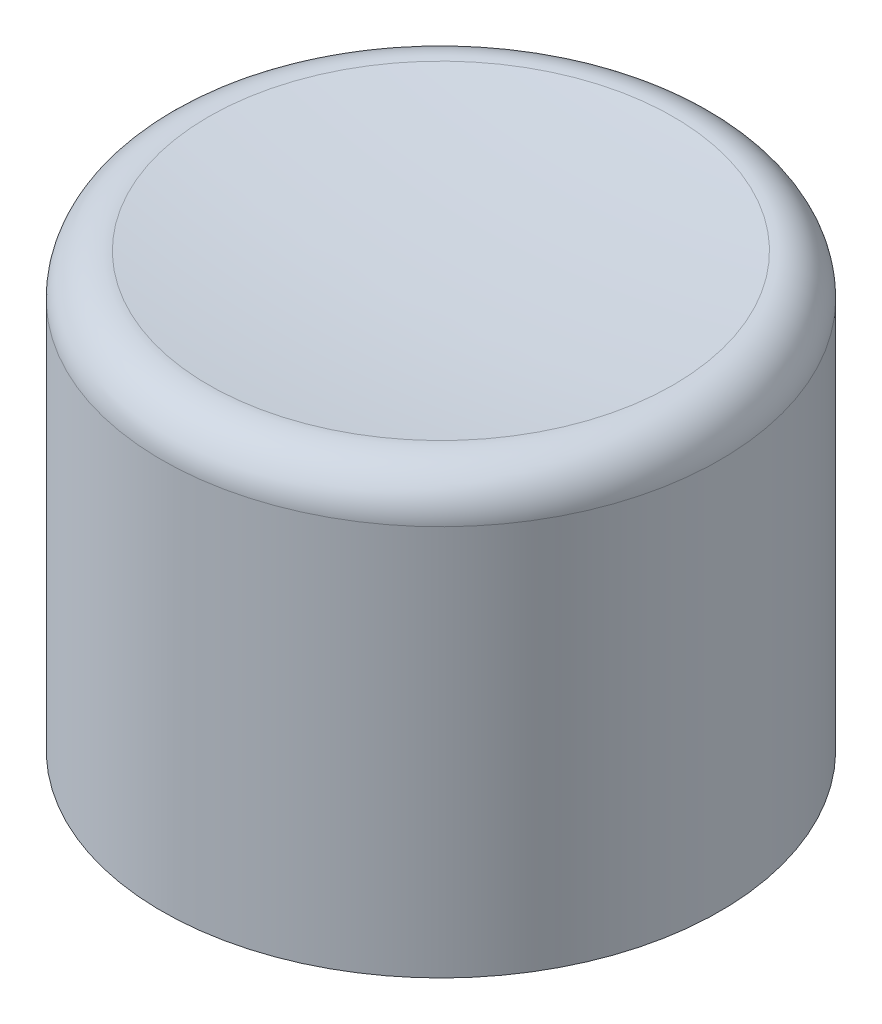
SolidWorks part; units mm, degrees
ref_plane "Front Plane" through (0, 0, 0) normal (0, 0, 1) x (1, 0, 0)
ref_plane "Top Plane" through (0, 0, 0) normal (0, 1, 0) x (1, 0, 0)
ref_plane "Right Plane" through (0, 0, 0) normal (1, 0, 0) x (0, 0, -1)
sketch "Sketch1" plane through (0, 0, 0) normal (0, 0, 1) x (1, 0, 0)
  line L0 (0, 0) -> (0, -66.4851) construction
  line L1 (55, 0) -> (-55, 0) construction
  line L2 (-1.5494, 0) -> (-1.5494, 3.048)
  line L3 (-1.5494, 3.048) -> (0, 3.048)
  line L6 (0, -55) -> (0, 55) construction
  line L7 (0, 3.048) -> (0, 3.81)
  line L8 (-2.54, 3.556) -> (-2.54, 0)
  line L9 (-2.54, 0) -> (-2.159, 0)
  line L10 (-2.159, 0) -> (-2.159, 3.048)
  line L11 (-2.159, 3.048) -> (-1.9304, 3.048)
  line L12 (-1.9304, 3.048) -> (-1.9304, 0)
  line L13 (-1.9304, 0) -> (-1.5494, 0)
  line L14 (0, 3.81) -> (3.3062, 3.81) construction
  arc A0 (-2.54, 3.556) -> (-2.1143, 3.9344) centre (-2.159, 3.556) cw
  arc A1 (-2.1143, 3.9344) -> (0, 3.81) centre (0, 21.844) ccw
  dimension "D4" = 0.381
  dimension "D5" = 3.937
  dimension "D9" = 0.381
  dimension "D1" = 5.08
  dimension "D2" = 3.0988
  dimension "D3" = 3.048
  dimension "D6" = 0.381
  dimension "D7" = 0.2286
  dimension "D8" = 3.81
revolve "Revolve1" add sketch "Sketch1" angle 360 about L0
